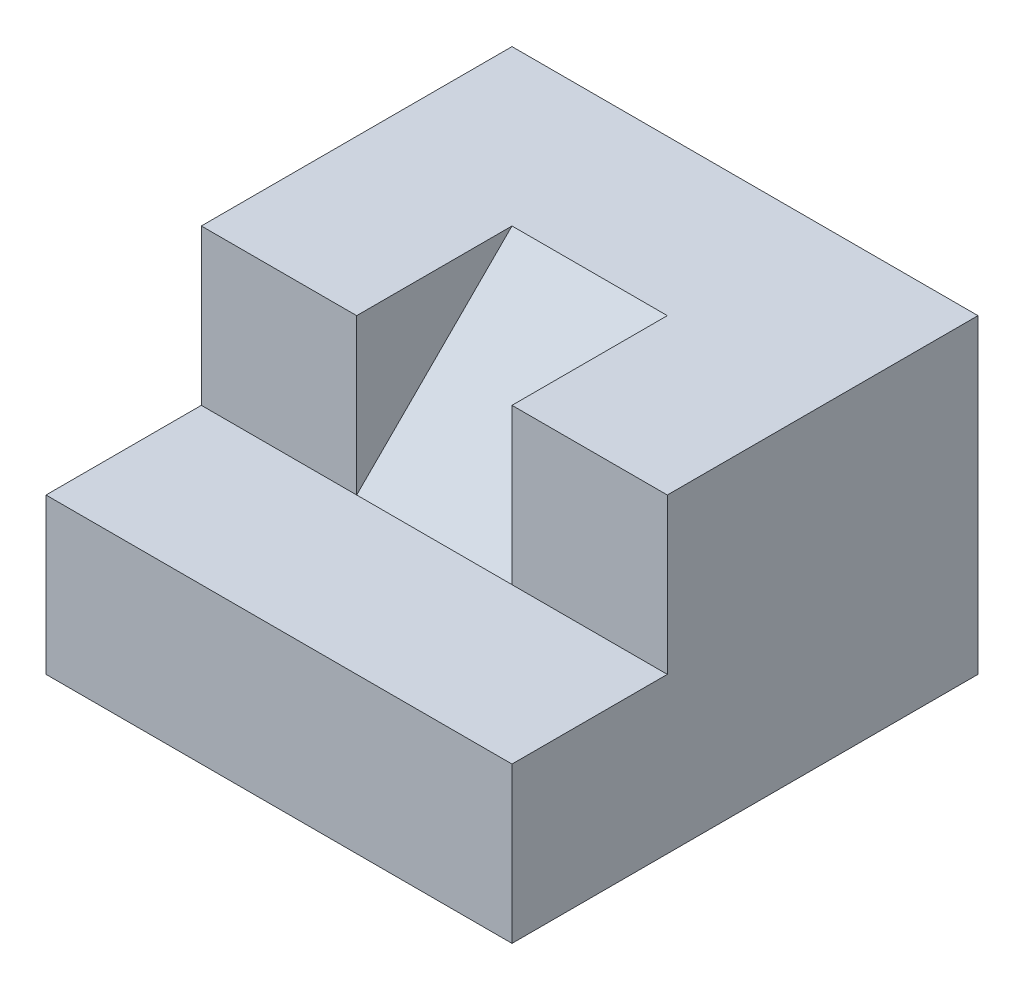
SolidWorks part; units mm, degrees
ref_plane "Front Plane" through (0, 0, 0) normal (0, 0, 1) x (1, 0, 0)
ref_plane "Top Plane" through (0, 0, 0) normal (0, 1, 0) x (1, 0, 0)
ref_plane "Right Plane" through (0, 0, 0) normal (1, 0, 0) x (0, 0, -1)
sketch "Sketch10" plane through (0, 0, 0) normal (0, 1, 0) x (1, 0, 0)
  line L1 (-30, -30) -> (30, -30)
  line L2 (-30, -30) -> (-30, 30)
  line L3 (-30, 30) -> (30, 30)
  line L4 (30, -30) -> (30, 30)
  line L5 (-30, -30) -> (30, 30) construction
  line L6 (-30, 30) -> (30, -30) construction
  point P0 (0, 0)
  dimension "D1" = 60
  dimension "D2" = 60
extrude "Boss-Extrude6" add sketch "Sketch10" along normal blind 40
sketch "Sketch12" plane through (0, 0, 30) normal (0, 0, 1) x (1, 0, 0)
  line L0 (30, 40) -> (30, 0) construction
  line L1 (-30, 40) -> (30, 40)
  line L2 (-30, 40) -> (-30, 20)
  line L3 (-30, 20) -> (30, 20)
  line L4 (30, 40) -> (30, 20)
  dimension "D1" = 20
extrude "Cut-Extrude4" cut sketch "Sketch12" against normal blind 20
sketch "Sketch25" plane through (30, 0, 0) normal (1, 0, 0) x (0, 0, -1)
  line L0 (-10, 20) -> (30.8299, 20) construction
  line L1 (10, 42.7962) -> (10, -5.0273) construction
  line L2 (-10, 20) -> (10, 40)
  line L3 (-10, 40) -> (30, 40) construction
  dimension "D1" = 20
extrude "Cut-Extrude7" cut sketch "Sketch25" against normal through all and the other way through all
sketch "Sketch26" plane through (0, 20, 0) normal (0, 1, 0) x (1, 0, 0)
  line L0 (-30, 10) -> (-30, -10)
  line L1 (-30, -10) -> (-10, -10)
  line L2 (-30, -10) -> (30, -10) construction
  line L3 (-10, -10) -> (-10, 10)
  line L4 (30, 10) -> (-30, 10) construction
  line L5 (-10, 10) -> (-30, 10)
  dimension "D1" = 20
extrude "Boss-Extrude8" add sketch "Sketch26" along normal blind 20
sketch "Sketch30" plane through (0, 20, 0) normal (0, 1, 0) x (1, 0, 0)
  line L0 (30, -10) -> (30, 10)
  line L1 (30, 10) -> (10, 10)
  line L2 (30, 10) -> (-10, 10) construction
  line L3 (10, 10) -> (10, -10)
  line L4 (-10, -10) -> (30, -10) construction
  line L5 (10, -10) -> (30, -10)
extrude "Boss-Extrude10" add sketch "Sketch30" along normal blind 20
